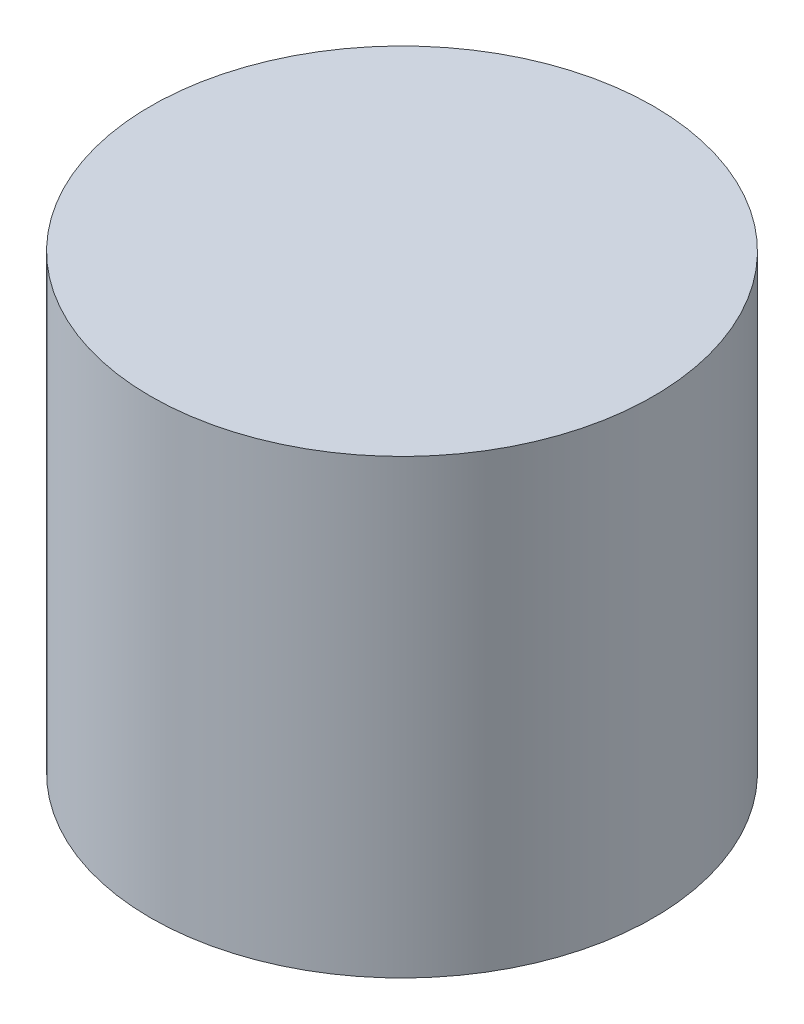
SolidWorks part; units mm, degrees
ref_plane "Front Plane" through (0, 0, 0) normal (0, 0, 1) x (1, 0, 0)
ref_plane "Top Plane" through (0, 0, 0) normal (0, 1, 0) x (1, 0, 0)
ref_plane "Right Plane" through (0, 0, 0) normal (1, 0, 0) x (0, 0, -1)
sketch "Sketch1" plane through (0, 0, 0) normal (0, 1, 0) x (1, 0, 0)
  circle A0 centre (0, 0) radius 5.565
  dimension "D1" = 11.13
extrude "Boss-Extrude1" add sketch "Sketch1" along normal blind 10
